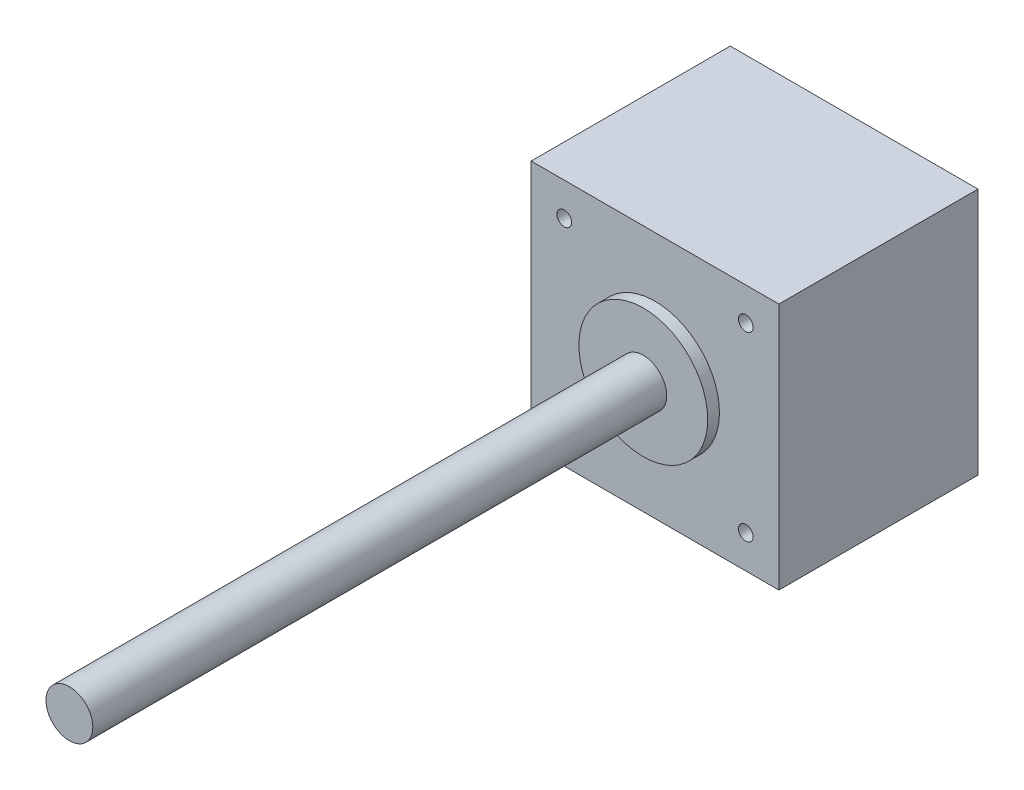
SolidWorks part; units mm, degrees
ref_plane "前视基准面" through (0, 0, 0) normal (0, 0, 1) x (1, 0, 0)
ref_plane "上视基准面" through (0, 0, 0) normal (0, 1, 0) x (1, 0, 0)
ref_plane "右视基准面" through (0, 0, 0) normal (1, 0, 0) x (0, 0, -1)
other "Configuration Table"
sketch "草图1" plane through (0, 0, 0) normal (0, 0, 1) x (1, 0, 0)
  line L1 (21.15, -21.15) -> (-21.15, -21.15)
  line L2 (21.15, -21.15) -> (21.15, 21.15)
  line L3 (21.15, 21.15) -> (-21.15, 21.15)
  line L4 (-21.15, -21.15) -> (-21.15, 21.15)
  line L5 (21.15, -21.15) -> (-21.15, 21.15) construction
  line L6 (21.15, 21.15) -> (-21.15, -21.15) construction
  point P0 (0, 0)
  dimension "D1" = 42.3
  dimension "D2" = 42.3
extrude "凸台-拉伸1" add sketch "草图1" along normal blind 34
sketch "草图2" plane through (0, 0, 34) normal (0, 0, 1) x (1, 0, 0)
  circle A0 centre (0, 0) radius 11
  dimension "D1" = 22
extrude "凸台-拉伸2" add sketch "草图2" along normal blind 2
sketch "草图3" plane through (0, 0, 36) normal (0, 0, 1) x (1, 0, 0)
  circle A0 centre (0, 0) radius 4
extrude "凸台-拉伸3" add sketch "草图3" along normal blind 98
sketch "草图4" plane through (0, 0, 34) normal (0, 0, 1) x (1, 0, 0)
  line L0 (-21.15, 21.15) -> (-21.15, -21.15) construction
  line L2 (21.15, 21.15) -> (-21.15, 21.15) construction
  line L3 (-21.15, -21.15) -> (21.15, -21.15) construction
  point P0 (-15.5, 15.5)
  point P1 (15.5, 15.5)
  point P2 (-15.5, -15.5)
  point P3 (15.5, -15.5)
  point P10 (0, 0)
  point P12 (-5.9342, -17.4964)
  dimension "D1" = 31
  dimension "D2" = 5.65
  dimension "D3" = 5.65
  dimension "D4" = 5.65
  dimension "D5" = 5.65
  dimension "D6" = 5.65
  dimension "D7" = 31
  dimension "D8" = 5.65
sketch "草图5" plane through (0, 0, 34) normal (0, 0, 1) x (1, 0, 0)
  point P0 (-15.5, 15.5)
  point P3 (15.5, 15.5)
  point P6 (15.5, -15.5)
  point P9 (-15.5, -15.5)
hole_wizard "M3 螺纹孔1" positions "草图5" profile "草图6" tap size "M3" standard "GB" end condition through all
sketch "草图6" plane through (-15.5, 15.5, 34) normal (1, 0, 0) x (0, -1, 0)
  line L0 (0, 0) -> (0, 34)
  line L1 (0, 34) -> (1.25, 34)
  line L2 (1.25, 34) -> (1.25, 0)
  line L5 (1.25, 0) -> (0, 0)
  line L11 (0, -6.35) -> (0, 107.95) construction
  dimension "通孔螺纹孔钻头直径" = 2.5
  dimension "通孔螺纹孔钻头深度" = 34
cosmetic thread "孔螺蚊线1" parameters "D2"=3
cosmetic thread "孔螺蚊线2" parameters "D2"=3
cosmetic thread "孔螺蚊线3" parameters "D2"=3
cosmetic thread "孔螺蚊线4" parameters "D2"=3
